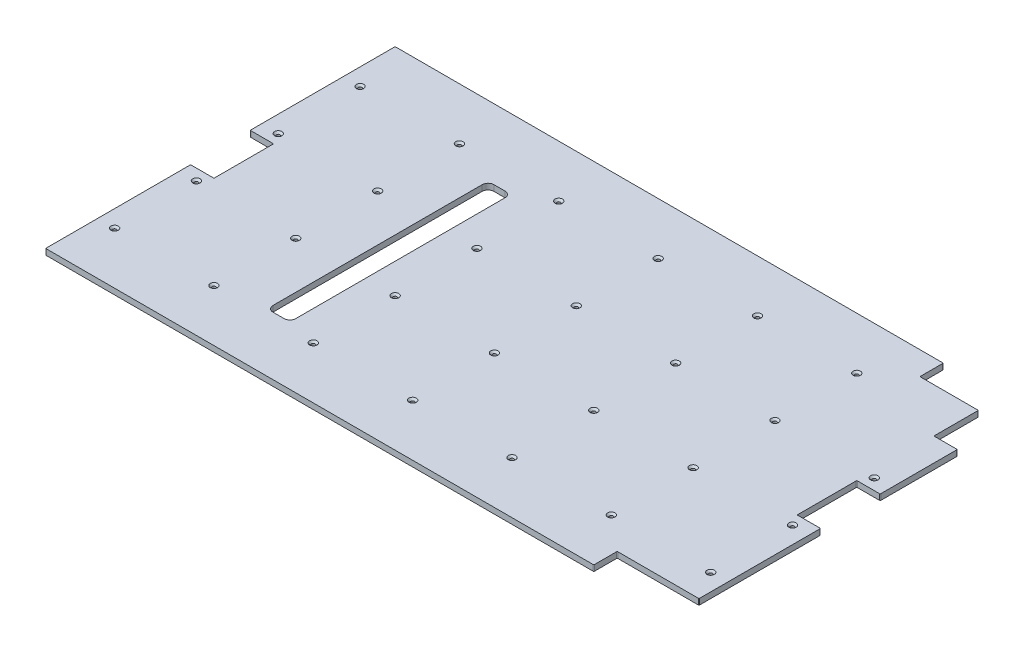
SolidWorks part; units mm, degrees
ref_plane "Front Plane" through (0, 0, 0) normal (0, 0, 1) x (1, 0, 0)
ref_plane "Top Plane" through (0, 0, 0) normal (0, 1, 0) x (1, 0, 0)
ref_plane "Right Plane" through (0, 0, 0) normal (1, 0, 0) x (0, 0, -1)
sketch "Sketch1" plane through (0, 0, 0) normal (0, 1, 0) x (1, 0, 0)
  line L1 (269.5, -149.5) -> (-269.5, -149.5)
  line L2 (269.5, -149.5) -> (269.5, 149.5)
  line L3 (269.5, 149.5) -> (-269.5, 149.5)
  line L4 (-269.5, -149.5) -> (-269.5, 149.5)
  line L5 (269.5, -149.5) -> (-269.5, 149.5) construction
  line L6 (269.5, 149.5) -> (-269.5, -149.5) construction
  point P0 (0, 0)
  dimension "D1" = 539
  dimension "D2" = 299
extrude "Boss-Extrude1" add sketch "Sketch1" along normal blind 5
sketch "Sketch2" plane through (0, 5, 0) normal (0, 1, 0) x (1, 0, 0)
  line L0 (0, 0) -> (-269.5, 0) construction
  line L1 (-269.5, 149.5) -> (-269.5, -149.5) construction
  line L3 (-249.5, -25.5) -> (-269.5, -25.5)
  line L4 (-249.5, -25.5) -> (-249.5, 25.5)
  line L5 (-249.5, 25.5) -> (-269.5, 25.5)
  line L6 (-269.5, -25.5) -> (-269.5, 25.5)
  line L7 (-249.5, -25.5) -> (-269.5, 25.5) construction
  line L8 (-249.5, 25.5) -> (-269.5, -25.5) construction
  point P5 (-259.5, 0)
  dimension "D1" = 20
  dimension "D2" = 51
extrude "Cut-Extrude1" cut sketch "Sketch2" against normal through all
mirror "Mirror1" about plane through (0, 0, 0) normal (1, 0, 0) of "Cut-Extrude1"
sketch "Sketch3" plane through (0, 5, 0) normal (0, 1, 0) x (1, 0, 0)
  point P0 (-255, -105)
  dimension "D1" = 255
  dimension "D2" = 105
hole_wizard "CSK for M3 Flat Head Machine Screw1" positions "3DSketch1" profile "Sketch4" countersink size "M3" standard "ANSI Metric" end condition through all
sketch3d "3DSketch1"
  point P0 (-255, 5, 105)
sketch "Sketch4" plane through (-255, 5, 105) normal (1, 0, 0) x (0, 0, 1)
  line L0 (0, 0) -> (0, 5)
  line L1 (0, 5) -> (1.6, 5)
  line L2 (1.6, 5) -> (1.6, 1.55)
  line L3 (1.6, 1.55) -> (3.15, 0)
  line L5 (3.15, 0) -> (0, 0)
  line L6 (-1.6, 1.55) -> (-3.15, 0) construction
  line L11 (0, -6.35) -> (0, 107.95) construction
  dimension "Thru Hole Dia." = 3.2
  dimension "Thru Hole Depth" = 5
  dimension "Near C'Sink Dia." = 6.3
  dimension "Near C'Sink Angle" = 90
pattern_linear "LPattern1" count 7 spacing 85 along (1, 0, 0) count 4 spacing 70 along (0, 0, -1) of "CSK for M3 Flat Head Machine Screw1"
sketch "Sketch5" plane through (0, 5, 0) normal (0, 1, 0) x (1, 0, 0)
  line L0 (-130, -99.5) -> (-130, 83.5) construction
  line L1 (-110.5, 89.5) -> (-110.5, -93.5) construction
  line L2 (-130, -94.5) -> (-130, 83.5)
  line L3 (-110.5, 84.5) -> (-110.5, -93.5)
  line L4 (-115.5, 89.5) -> (-125, 89.5)
  line L5 (-234.5, 89.5) -> (-110.5, 89.5) construction
  line L6 (-130, 84.5) -> (-130, 83.5)
  line L7 (-125, -99.5) -> (-115.5, -99.5)
  line L8 (-130, -99.5) -> (-95, -99.5) construction
  line L9 (-110.5, -94.5) -> (-110.5, -93.5)
  arc A0 (-125, 89.5) -> (-130, 84.5) centre (-125, 84.5) ccw
  arc A1 (-130, -94.5) -> (-125, -99.5) centre (-125, -94.5) ccw
  arc A2 (-115.5, -99.5) -> (-110.5, -94.5) centre (-115.5, -94.5) ccw
  arc A3 (-110.5, 84.5) -> (-115.5, 89.5) centre (-115.5, 84.5) ccw
  point P12 (-130, 89.5)
  point P18 (-110.5, -99.5)
  dimension "D1" = 5
extrude "Cut-Extrude2" cut sketch "Sketch5" against normal through all
sketch "Sketch6" plane through (0, 5, 0) normal (0, 1, 0) x (1, 0, 0)
  line L0 (199.5, 149.5) -> (199.5, 129.5)
  line L1 (269.5, 149.5) -> (-269.5, 149.5) construction
  line L2 (199.5, 129.5) -> (249.5, 129.5)
  line L3 (249.5, 129.5) -> (249.5, 91.5)
  line L4 (249.5, 91.5) -> (269.5, 91.5)
  line L6 (269.5, 25.5) -> (269.5, 149.5) construction
  line L7 (199.5, 149.5) -> (269.5, 149.5)
  line L8 (269.5, -149.5) -> (199.5, -149.5)
  line L9 (269.5, -149.5) -> (269.5, -129.5)
  line L10 (269.5, -129.5) -> (199.5, -129.5)
  line L11 (199.5, -149.5) -> (199.5, -129.5)
  line L12 (269.5, 149.5) -> (269.5, 91.5)
  dimension "D1" = 58
  dimension "D2" = 20
  dimension "D3" = 70
  dimension "D4" = 20
  dimension "D5" = 70
  dimension "D6" = 20
extrude "Cut-Extrude3" cut sketch "Sketch6" against normal through all and the other way through all
fillet "Fillet1" radius 0.5 18 edges at (249.5, 2.5, -129.5) (199.5, 2.5, -129.5) (199.5, 2.5, -149.5) (-269.5, 2.5, -149.5) (-249.5, 2.5, -25.5) (-249.5, 2.5, 25.5) (-269.5, 2.5, 25.5) (-269.5, 2.5, 149.5) (199.5, 2.5, 149.5) (199.5, 2.5, 129.5) (269.5, 2.5, 129.5) (269.5, 2.5, 25.5) (249.5, 2.5, 25.5) (249.5, 2.5, -25.5) (269.5, 2.5, -25.5) (269.5, 2.5, -91.5) (249.5, 2.5, -91.5) (-269.5, 2.5, -25.5)
